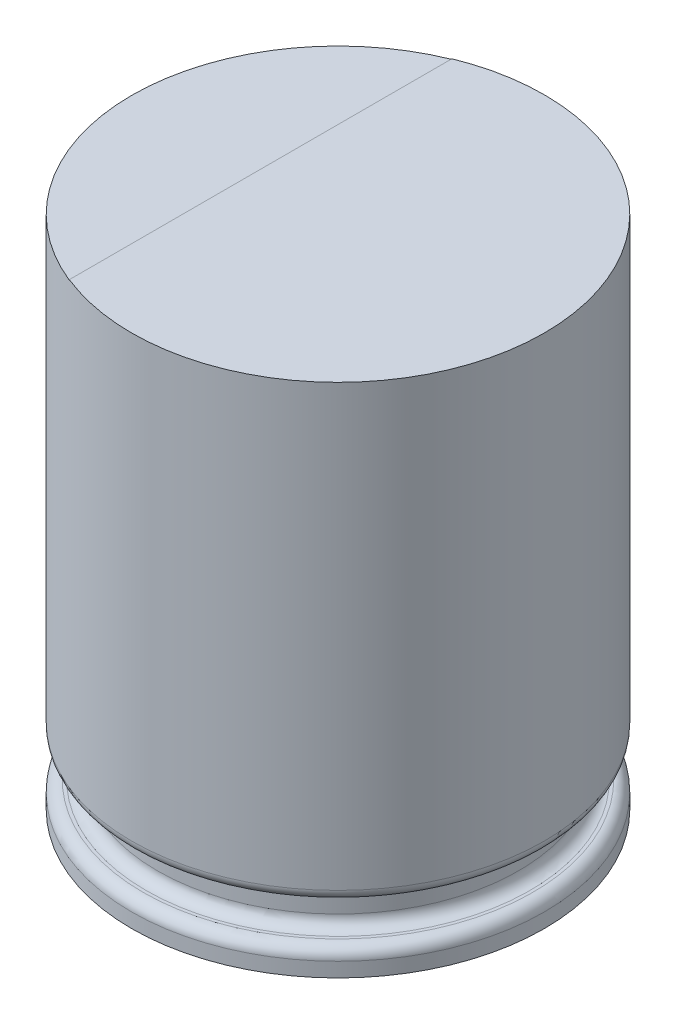
SolidWorks part; units mm, degrees
ref_plane "Front Plane" through (0, 0, 0) normal (0, 0, 1) x (1, 0, 0)
ref_plane "Top Plane" through (0, 0, 0) normal (0, 1, 0) x (1, 0, 0)
ref_plane "Right Plane" through (0, 0, 0) normal (1, 0, 0) x (0, 0, -1)
sketch "Sketch1" plane through (0, 0, 0) normal (0, 0, 1) x (1, 0, 0)
  line L0 (0, 0) -> (0, 10)
  line L1 (0, 10) -> (4, 10)
  line L2 (4, 10) -> (4, 1.47)
  line L3 (3.78, 1.25) -> (3.72, 1.25)
  line L4 (3.5, 1.03) -> (3.5, 0.72)
  line L5 (3.72, 0.5) -> (3.78, 0.5)
  line L6 (4, 0.28) -> (4, 0)
  line L7 (4, 0) -> (0, 0)
  line L8 (0, 10) -> (0, 0) construction
  arc A0 (3.78, 0.5) -> (4, 0.28) centre (3.78, 0.28) cw
  arc A1 (3.5, 0.72) -> (3.72, 0.5) centre (3.72, 0.72) ccw
  arc A2 (3.72, 1.25) -> (3.5, 1.03) centre (3.72, 1.03) ccw
  arc A3 (4, 1.47) -> (3.78, 1.25) centre (3.78, 1.47) cw
  dimension "D2" = 0.22
  dimension "D1" = 10
  dimension "D3" = 0.5
  dimension "D4" = 4
  dimension "D5" = 0.5
  dimension "D6" = 0.75
revolve "Revolve1" add sketch "Sketch1" angle 360 about L8
sketch "Sketch2" plane through (0, 10, 0) normal (0, 1, 0) x (1, 0, 0)
  line L0 (-1.5, 3.7081) -> (-1.5, -3.7081)
  circle A1 centre (0, 0) radius 4
  arc A2 (-1.5, 3.7081) -> (-1.5, -3.7081) centre (0, 0) ccw
  dimension "D2" = 2.5
  dimension "D1" = 0
extrude "Cut-Extrude1" cut sketch "Sketch2" against normal blind 0.01
